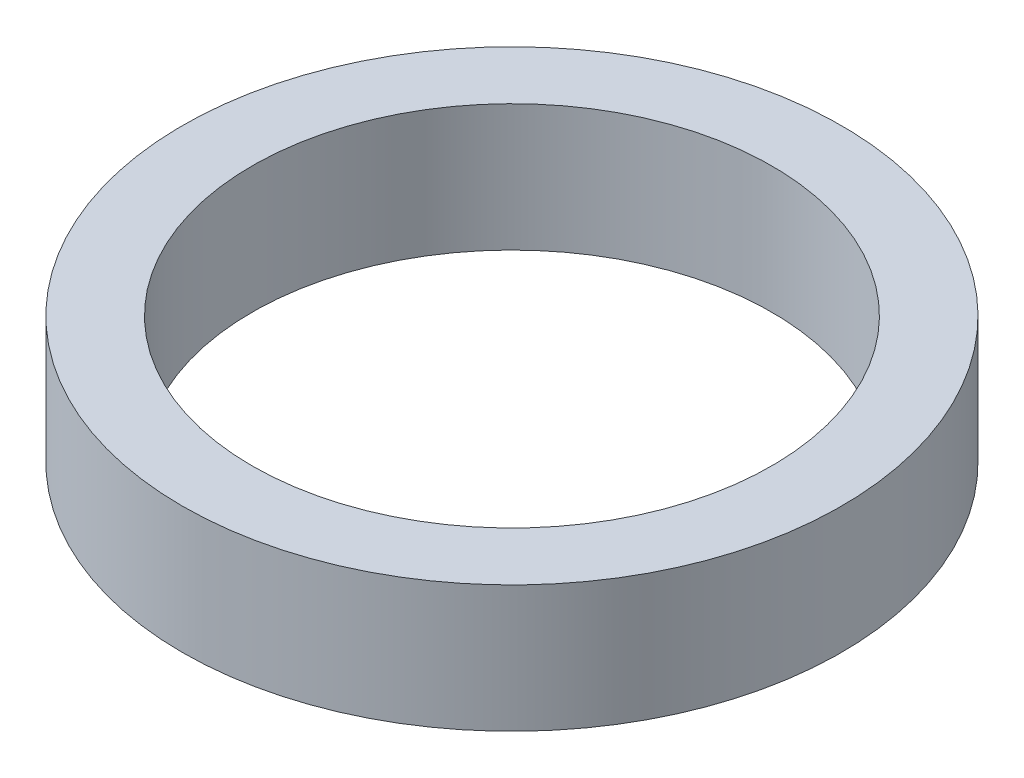
SolidWorks part; units mm, degrees
ref_plane "前视基准面" through (0, 0, 0) normal (0, 0, 1) x (1, 0, 0)
ref_plane "上视基准面" through (0, 0, 0) normal (0, 1, 0) x (1, 0, 0)
ref_plane "右视基准面" through (0, 0, 0) normal (1, 0, 0) x (0, 0, -1)
sketch "草图1" plane through (0, 0, 0) normal (0, 1, 0) x (1, 0, 0)
  circle A0 centre (0, 0) radius 2.05
  circle A1 centre (0, 0) radius 2.6
  dimension "D1" = 4.1
  dimension "D2" = 5.2
extrude "凸台-拉伸1" add sketch "草图1" along normal blind 1
